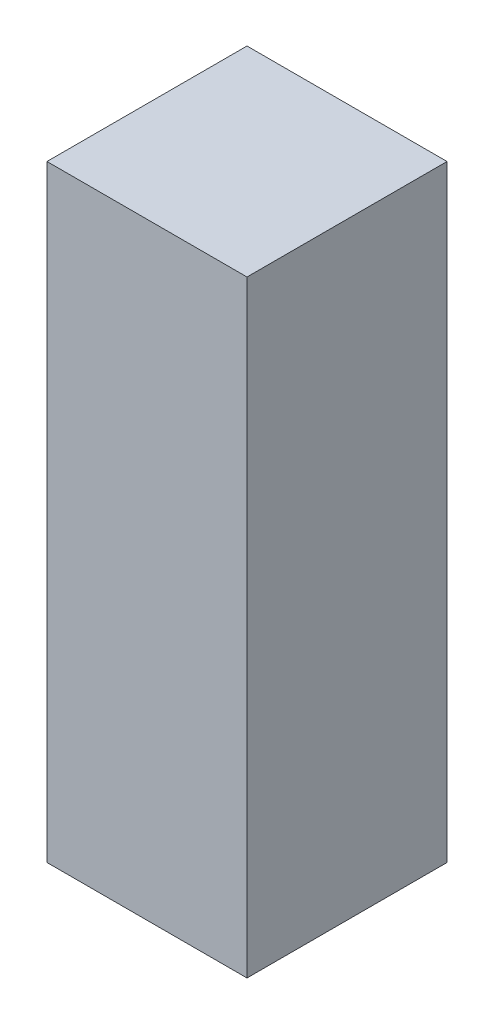
SolidWorks part; units mm, degrees
ref_plane "Front Plane" through (0, 0, 0) normal (0, 0, 1) x (1, 0, 0)
ref_plane "Top Plane" through (0, 0, 0) normal (0, 1, 0) x (1, 0, 0)
ref_plane "Right Plane" through (0, 0, 0) normal (1, 0, 0) x (0, 0, -1)
sketch "Sketch1" plane through (0, 0, 0) normal (0, 1, 0) x (1, 0, 0)
  line L1 (-50, -50) -> (50, -50)
  line L2 (-50, -50) -> (-50, 50)
  line L3 (-50, 50) -> (50, 50)
  line L4 (50, -50) -> (50, 50)
  line L5 (-50, -50) -> (50, 50) construction
  line L6 (-50, 50) -> (50, -50) construction
  point P0 (0, 0)
  dimension "D1" = 100
  dimension "D2" = 100
extrude "Boss-Extrude1" add sketch "Sketch1" along normal blind 303.5
ref_plane "Plane1" through (0, 151.75, 0) normal (0, 1, 0) x (1, 0, 0)
